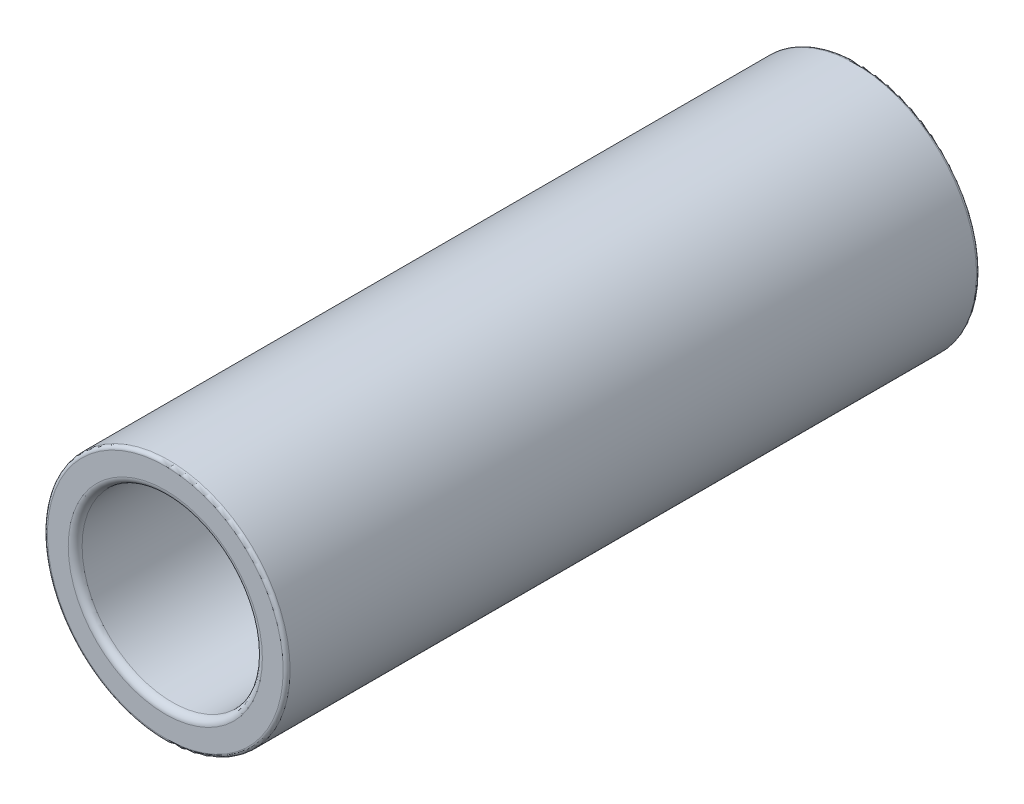
SolidWorks part; units mm, degrees
ref_plane "Alzado" through (0, 0, 0) normal (0, 0, 1) x (1, 0, 0)
ref_plane "Planta" through (0, 0, 0) normal (0, 1, 0) x (1, 0, 0)
ref_plane "Vista lateral" through (0, 0, 0) normal (1, 0, 0) x (0, 0, -1)
sketch "Croquis1" plane through (0, 0, 0) normal (0, 0, 1) x (1, 0, 0)
  circle A0 centre (0, 0) radius 2.6
  circle A1 centre (0, 0) radius 3.5
  dimension "D1" = 5.2
  dimension "D2" = 7
extrude "Saliente-Extruir2" add sketch "Croquis1" along normal blind 20
fillet "Redondeo5" radius 0.1 2 edges at (3.5, 0, 0) (3.5, 0, 20)
fillet "Redondeo6" radius 0.2 2 edges at (2.6, 0, 0) (2.6, 0, 20)
